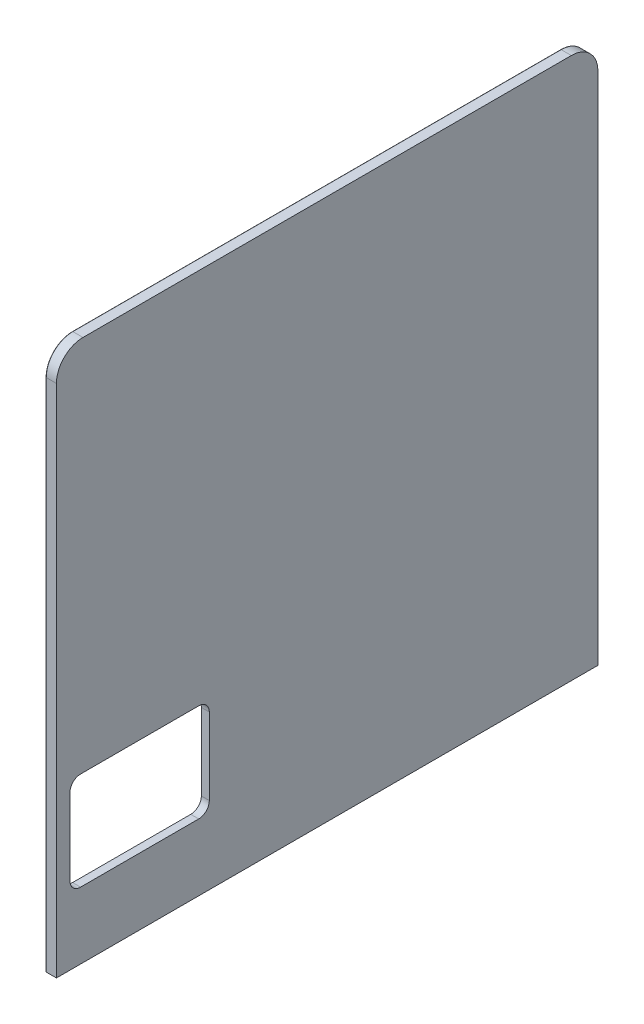
SolidWorks part; units mm, degrees
ref_plane "Front Plane" through (0, 0, 0) normal (0, 0, 1) x (1, 0, 0)
ref_plane "Top Plane" through (0, 0, 0) normal (0, 1, 0) x (1, 0, 0)
ref_plane "Right Plane" through (0, 0, 0) normal (1, 0, 0) x (0, 0, -1)
sketch "Sketch1" plane through (0, 0, 0) normal (1, 0, 0) x (0, 0, -1)
  line L1 (-102, -102) -> (102, -102)
  line L2 (-102, -102) -> (-102, 92)
  line L3 (-92, 102) -> (92, 102)
  line L4 (102, -102) -> (102, 92)
  line L5 (-102, -102) -> (102, 102) construction
  line L6 (-102, 102) -> (102, -102) construction
  arc A2 (-102, 92) -> (-92, 102) centre (-92, 92) cw
  arc A3 (92, 102) -> (102, 92) centre (92, 92) cw
  point P0 (0, 0)
  dimension "D1" = 204
  dimension "D2" = 204
extrude "Boss-Extrude1" add sketch "Sketch1" along normal blind 4
sketch "Sketch2" plane through (4, 0, 0) normal (1, 0, 0) x (0, 0, -1)
  line L1 (92, 102) -> (-92, 102) construction
  line L37 (102, -102) -> (102, 92) construction
  line L40 (-100.1, 90.3) -> (-100.1, -70.3)
  line L41 (-90.3, 100.1) -> (90.3, 100.1)
  line L42 (100.1, 90.3) -> (100.1, -90.3)
  line L43 (90.3, -100.1) -> (-100.1, -100.1)
  line L44 (-100.1, -100.1) -> (-100.1, -98.7)
  line L45 (-97.3, -95.9) -> (85.7, -95.9)
  line L46 (85.7, 95.9) -> (-85.7, 95.9)
  line L47 (-95.9, 85.7) -> (-95.9, -35.8)
  line L48 (-90.9, -75.9) -> (-48.4, -75.9)
  line L49 (75.9, -65.7) -> (75.9, 78)
  line L50 (-90.3, -80.1) -> (70.3, -80.1)
  line L51 (95.9, -85.7) -> (95.9, 85.7)
  line L52 (80.1, 78) -> (80.1, -70.3)
  line L53 (-92.9, -41) -> (-49.4, -41)
  line L54 (-45.4, -45) -> (-45.4, -61)
  line L55 (-43.2, -72.9) -> (-43.2, -42.8)
  line L56 (-47.2, -38.8) -> (-92.9, -38.8)
  line L57 (-95.9, -44) -> (-95.9, -61)
  line L58 (-40.2, -75.9) -> (65.7, -75.9)
  line L59 (-95.9, -61) -> (-94.9, -61)
  line L60 (-94.9, -61) -> (-94.9, -62.5)
  line L61 (-94.9, -62.5) -> (-95.9, -62.5)
  line L62 (-95.9, -64.4) -> (-94.9, -64.4)
  line L63 (-94.9, -64.4) -> (-94.9, -65.9)
  line L64 (-94.9, -65.9) -> (-95.9, -65.9)
  line L65 (-95.9, -62.5) -> (-95.9, -64.4)
  line L66 (-95.9, -65.9) -> (-95.9, -70.9)
  line L67 (-45.4, -61) -> (-46.4, -61)
  line L68 (-46.4, -61) -> (-46.4, -62.5)
  line L69 (-46.4, -62.5) -> (-45.4, -62.5)
  line L70 (-45.4, -65.9) -> (-46.4, -65.9)
  line L71 (-46.4, -65.9) -> (-46.4, -64.4)
  line L72 (-46.4, -64.4) -> (-45.4, -64.4)
  line L73 (-45.4, -62.5) -> (-45.4, -64.4)
  line L74 (-45.4, -65.9) -> (-45.4, -72.9)
  arc A32 (-95.9, -70.9) -> (-90.9, -75.9) centre (-90.9, -70.9) ccw
  arc A33 (65.7, -75.9) -> (75.9, -65.7) centre (65.7, -65.7) ccw
  arc A34 (-85.7, 95.9) -> (-95.9, 85.7) centre (-85.7, 85.7) ccw
  arc A35 (-100.1, 90.3) -> (-90.3, 100.1) centre (-90.3, 90.3) cw
  arc A36 (100.1, -90.3) -> (90.3, -100.1) centre (90.3, -90.3) cw
  arc A37 (85.7, -95.9) -> (95.9, -85.7) centre (85.7, -85.7) ccw
  arc A38 (80.1, -70.3) -> (70.3, -80.1) centre (70.3, -70.3) cw
  arc A39 (85.7, 95.9) -> (95.9, 85.7) centre (85.7, 85.7) cw
  arc A40 (90.3, 100.1) -> (100.1, 90.3) centre (90.3, 90.3) cw
  arc A41 (75.9, 78) -> (80.1, 78) centre (78, 78) cw
  arc A42 (-100.1, -98.7) -> (-97.3, -95.9) centre (-97.3, -98.7) cw
  arc A43 (-100.1, -70.3) -> (-90.3, -80.1) centre (-90.3, -70.3) ccw
  arc A44 (-43.2, -42.8) -> (-47.2, -38.8) centre (-47.2, -42.8) ccw
  arc A45 (-49.4, -41) -> (-45.4, -45) centre (-49.4, -45) cw
  arc A46 (-40.2, -75.9) -> (-43.2, -72.9) centre (-40.2, -72.9) cw
  arc A47 (-92.9, -38.8) -> (-95.9, -35.8) centre (-92.9, -35.8) cw
  arc A48 (-45.4, -72.9) -> (-48.4, -75.9) centre (-48.4, -72.9) cw
  arc A49 (-92.9, -41) -> (-95.9, -44) centre (-92.9, -44) ccw
  point P63 (-95.4, -64.4)
  dimension "D19" = 2.1
  dimension "D26" = 4
  dimension "D27" = 3
  dimension "D5" = 4.2
  dimension "D9" = 9.8
  dimension "D24" = 2.2
  dimension "D33" = 1.9
  dimension "D34" = 1
  dimension "D35" = 50.5
  dimension "D15" = 10.2
  dimension "D16" = 9.8
  dimension "D17" = 10.2
  dimension "D18" = 9.8
  dimension "D12" = 4.2
  dimension "D13" = 15.8
  dimension "D6" = 10.2
  dimension "D7" = 10.2
  dimension "D8" = 9.8
  dimension "D21" = 2.8
  dimension "D22" = 9.8
  dimension "D23" = 5
  dimension "D28" = 3
  dimension "D1" = 4.2
  dimension "D2" = 4.2
  dimension "D3" = 4.2
  dimension "D4" = 15.8
  dimension "D10" = 200.2
  dimension "D11" = 200.2
  dimension "D14" = 4.2
  dimension "D20" = 15.8
  dimension "D25" = 2.2
  dimension "D29" = 1.5
  dimension "D30" = 1.9
  dimension "D31" = 1
  dimension "D32" = 20
  dimension "D36" = 34.9
  dimension "D37" = 1.9
  dimension "D38" = 1.9
extrude "Cut-Extrude3" cut sketch "Sketch2" along normal blind 1 from surface at -4 starting at face at (0, 31.357, 0)
fillet "Fillet1" radius 0.2 59 edges at (0, 99.0711, -99.0711) (0, 102, 0) (0, 99.0711, 99.0711) (0, -5, 102) (0, -102, 0) (0, -5, -102) (0, 0, -100.1) (0, -96.7201, 99.2799) (0, -95.9, 5.8) (0, -92.9125, -92.9125) (0, 0, -95.9) (0, 92.9125, -92.9125) (0, 95.9, 0) (0, 92.9125, 92.9125) (0, 24.95, 95.9) (0, -37.9213, 95.0213) (0, -38.8, 70.05) (0, -39.9716, 44.3716) (0, -57.85, 43.2) (0, -75.0213, 42.3213) (0, -75.9, -12.75) (0, -72.9125, -72.9125) (0, 6.15, -75.9) (0, 80.1, -78) (0, 3.85, -80.1) (0, -77.2296, -77.2296) (0, -80.1, 10) (0, -77.2296, 97.2296) (0, 10, 100.1) (0, 97.2296, 97.2296) (0, 100.1, 0) (0, 97.2296, -97.2296) (0, -97.2296, -97.2296) (0, -100.1, 4.9) (0, -99.4, 100.1) (0, -68.4, 95.9) (0, -74.4355, 94.4355) (0, -75.9, 69.65) (0, -75.0213, 46.2787) (0, -69.4, 45.4) (0, -65.9, 45.9) (0, -65.15, 46.4) (0, -64.4, 45.9) (0, -63.45, 45.4) (0, -62.5, 45.9) (0, -61.75, 46.4) (0, -61, 45.9) (0, -53, 45.4) (0, -42.1716, 46.5716) (0, -41, 71.15) (0, -41.8787, 95.0213) (0, -52.5, 95.9) (0, -61, 95.4) (0, -61.75, 94.9) (0, -62.5, 95.4) (0, -63.45, 95.9) (0, -64.4, 95.4) (0, -65.15, 94.9) (0, -65.9, 95.4)
sketch "Sketch4" plane through (4, 0, 0) normal (1, 0, 0) x (0, 0, -1)
  line L1 (-92.9, -40) -> (-48.4, -40)
  line L2 (-96.9, -44) -> (-96.9, -72.9)
  line L3 (-92.9, -76.9) -> (-48.4, -76.9)
  line L4 (-44.4, -44) -> (-44.4, -72.9)
  line L6 (-92.9, -41) -> (-49.4, -41) construction
  line L7 (-90.9, -75.9) -> (-48.4, -75.9) construction
  line L8 (-45.4, -45) -> (-45.4, -61) construction
  line L9 (-95.9, -44) -> (-95.9, -61) construction
  arc A2 (-48.4, -76.9) -> (-44.4, -72.9) centre (-48.4, -72.9) ccw
  arc A3 (-96.9, -72.9) -> (-92.9, -76.9) centre (-92.9, -72.9) ccw
  arc A4 (-48.4, -40) -> (-44.4, -44) centre (-48.4, -44) cw
  arc A5 (-92.9, -40) -> (-96.9, -44) centre (-92.9, -44) ccw
  dimension "D1" = 4
  dimension "D2" = 1
  dimension "D3" = 1
  dimension "D4" = 1
  dimension "D5" = 1
extrude "Cut-Extrude4" cut sketch "Sketch4" against normal up to next
